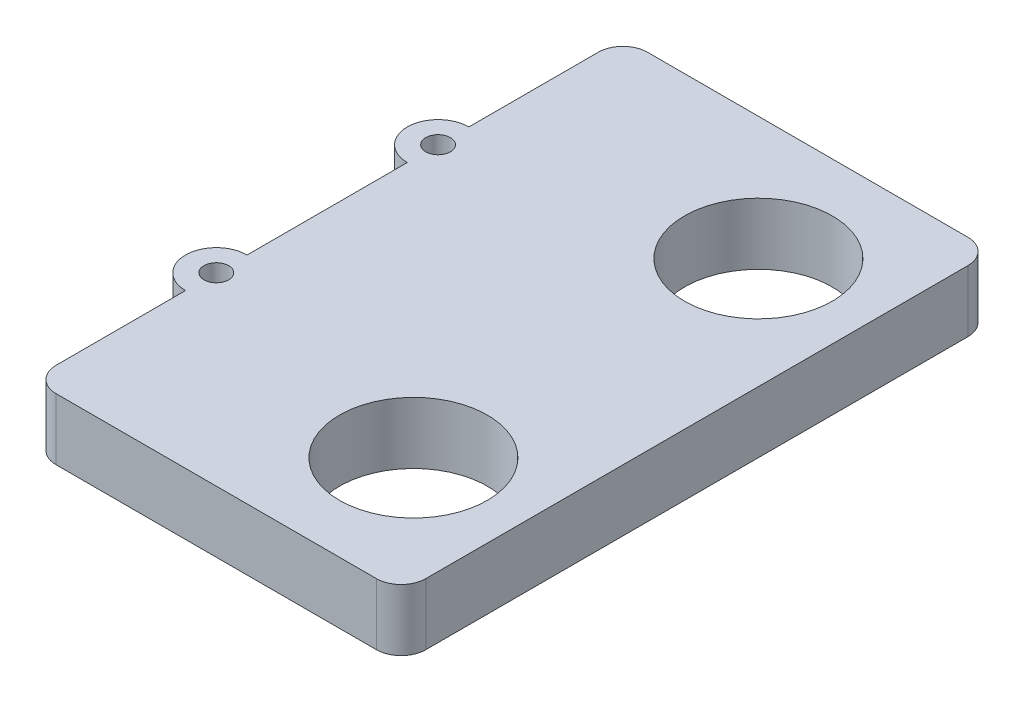
SolidWorks part; units mm, degrees
ref_plane "Front Plane" through (0, 0, 0) normal (0, 0, 1) x (1, 0, 0)
ref_plane "Top Plane" through (0, 0, 0) normal (0, 1, 0) x (1, 0, 0)
ref_plane "Right Plane" through (0, 0, 0) normal (1, 0, 0) x (0, 0, -1)
sketch "Sketch1" plane through (0, 0, 0) normal (0, 1, 0) x (1, 0, 0)
  line L0 (0, 0) -> (0, 12.5) construction
  line L1 (0, 0) -> (30, 0)
  line L3 (0, 48) -> (30, 48)
  line L4 (30, 0) -> (30, 48)
  line L5 (0, 0) -> (0, 12.5)
  line L6 (0, 35.5) -> (0, 48) construction
  line L7 (0, 35.5) -> (0, 48)
  line L8 (0, 17.5) -> (0, 30.5) construction
  line L9 (0, 17.5) -> (0, 30.5)
  circle A2 centre (21, 38) radius 6
  circle A3 centre (21, 10) radius 6
  arc A6 (0, 17.5) -> (0, 12.5) centre (0, 15) ccw
  arc A7 (0, 35.5) -> (0, 30.5) centre (0, 33) ccw
  circle A11 centre (0, 33) radius 1
  circle A12 centre (0, 15) radius 1
  dimension "D13" = 5
  dimension "D14" = 5
  dimension "D7" = 12
  dimension "D8" = 2
  dimension "D2" = 9
  dimension "D3" = 48
  dimension "D4" = 30
  dimension "D5" = 10
  dimension "D6" = 28
  dimension "D10" = 21
  dimension "D11" = 15
  dimension "D12" = 18
extrude "Boss-Extrude1" add sketch "Sketch1" along normal blind 5
fillet "Fillet2" radius 2 4 edges at (0, 2.5, 0) (30, 2.5, 0) (0, 2.5, -48) (30, 2.5, -48)
